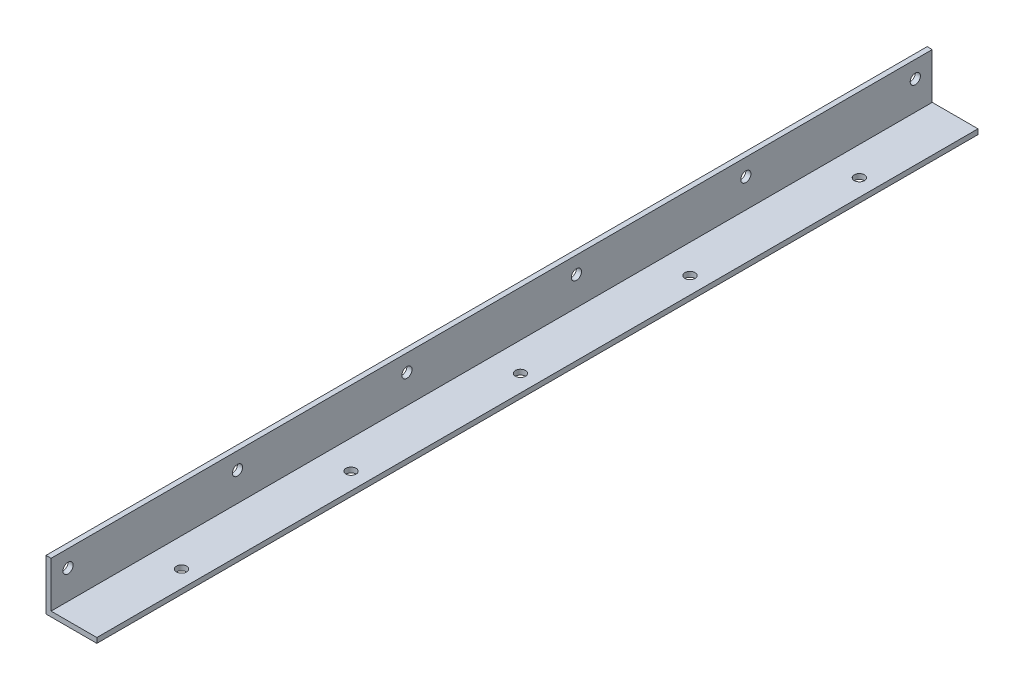
SolidWorks part; units mm, degrees
ref_plane "Plan de face" through (0, 0, 0) normal (0, 0, 1) x (1, 0, 0)
ref_plane "Plan de dessus" through (0, 0, 0) normal (0, 1, 0) x (1, 0, 0)
ref_plane "Plan de droite" through (0, 0, 0) normal (1, 0, 0) x (0, 0, -1)
sketch "Esquisse1" plane through (0, 0, 0) normal (0, 0, 1) x (1, 0, 0)
  line L1 (0, 0) -> (1.5, 0)
  line L2 (0, 0) -> (0, 15)
  line L3 (0, 15) -> (1.5, 15)
  line L4 (1.5, 1.5) -> (1.5, 15)
  line L5 (1.5, 0) -> (15, 0)
  line L7 (1.5, 1.5) -> (15, 1.5)
  line L8 (15, 0) -> (15, 1.5)
  dimension "D1" = 1.5
  dimension "D2" = 1.5
  dimension "D3" = 15
  dimension "D4" = 13.5
extrude "Extrusion1" add sketch "Esquisse1" along normal blind 260
sketch "Esquisse2" plane through (0, 0, 0) normal (-1, 0, 0) x (0, 0, 1)
  line L0 (0, 15) -> (0, 0) construction
  line L1 (260, 15) -> (0, 15) construction
  circle A0 centre (5, 10) radius 1.5
  dimension "D1" = 3
  dimension "D2" = 5
  dimension "D3" = 5
extrude "Extrusion2" cut sketch "Esquisse2" against normal through all
pattern_linear "Répétition linéaire1" count 6 spacing 50 along (0, 0, 1) of "Extrusion2"
sketch "Esquisse3" plane through (0, 0, 0) normal (0, -1, 0) x (1, 0, 0)
  line L0 (0, 0) -> (15, 0) construction
  line L1 (15, 260) -> (15, 0) construction
  circle A0 centre (10, 30) radius 1.5
  point P6 (14.7546, 38.0988)
  point P7 (18.1266, 42.6898)
  dimension "D1" = 3
  dimension "D2" = 30
  dimension "D3" = 5
extrude "Extrusion3" cut sketch "Esquisse3" against normal through all
pattern_linear "Répétition linéaire2" count 5 spacing 50 along (0, 0, 1) of "Extrusion3"
